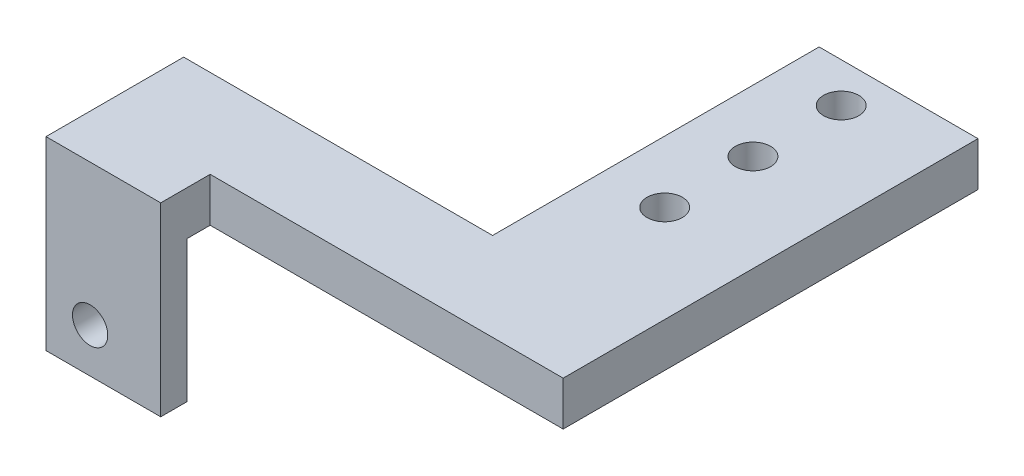
SolidWorks part; units mm, degrees
ref_plane "Alzado" through (0, 0, 0) normal (0, 0, 1) x (1, 0, 0)
ref_plane "Planta" through (0, 0, 0) normal (0, 1, 0) x (1, 0, 0)
ref_plane "Vista lateral" through (0, 0, 0) normal (1, 0, 0) x (0, 0, -1)
sketch "Croquis1" plane through (0, 0, 0) normal (0, 1, 0) x (1, 0, 0)
  line L0 (27.5, -11.1605) -> (-12.5, -11.1605)
  line L1 (-12.5, -16.7605) -> (-25.5, -16.7605)
  line L2 (27.5, -11.1605) -> (27.5, 35.8395)
  line L3 (27.5, 35.8395) -> (9.5, 35.8395)
  line L4 (-25.5, -16.7605) -> (-25.5, -1.1605)
  line L7 (-12.5, -11.1605) -> (-12.5, -16.7605)
  line L8 (-25.5, -1.1605) -> (9.5, -1.1605)
  line L9 (9.5, 35.8395) -> (9.5, -1.1605)
  point P0 (0, 0)
  dimension "D1" = 5.6
  dimension "D2" = 40
  dimension "D3" = 47
  dimension "D4" = 10
  dimension "D5" = 18
  dimension "D6" = 13
extrude "Saliente-Extruir1" add sketch "Croquis1" along normal blind 5
sketch "Croquis2" plane through (0, 0, 0) normal (0, -1, 0) x (-1, 0, 0)
  line L0 (25.5, -1.1605) -> (25.5, -16.7605) construction
  line L1 (12.5, -16.7605) -> (25.5, -16.7605)
  line L2 (12.5, -16.7605) -> (12.5, -13.7605)
  line L3 (12.5, -13.7605) -> (25.5, -13.7605)
  line L4 (25.5, -16.7605) -> (25.5, -13.7605)
  dimension "D1" = 3
extrude "Saliente-Extruir2" add sketch "Croquis2" along normal blind 16
sketch "Croquis3" plane through (0, 5, 0) normal (0, 1, 0) x (1, 0, 0)
  line L0 (14.5, -8.7441) -> (14.5, 49991.2559) construction
  line L1 (9.5, 35.8395) -> (9.5, -1.1605) construction
  line L2 (4.8587, 33.3395) -> (33.3046, 33.3395) construction
  line L3 (27.5, 35.8395) -> (9.5, 35.8395) construction
  line L4 (-8.5872, 21.3395) -> (5.6661, 21.3395) construction
  line L5 (-7.2297, 11.3395) -> (5.1725, 11.3395) construction
  circle A0 centre (16.5, 31.3395) radius 2
  circle A1 centre (16.5, 21.3395) radius 2
  circle A2 centre (16.5, 11.3395) radius 2
  dimension "D3" = 10
  dimension "D1" = 5
  dimension "D2" = 2.5
  dimension "D4" = 10
extrude "Cortar-Extruir1" cut sketch "Croquis3" against normal blind 16
sketch "Croquis7" plane through (0, 0, 13.7605) normal (0, 0, -1) x (-1, 0, 0)
  line L0 (18.1653, -13) -> (30.2995, -13) construction
  line L1 (22.5, -7.0168) -> (22.5, -17.2731) construction
  line L2 (25.5, -16) -> (25.5, 0) construction
  line L3 (25.5, -16) -> (12.5, -16) construction
  circle A0 centre (20.5, -11) radius 2
  dimension "D1" = 3
  dimension "D2" = 3
extrude "Cortar-Extruir2" cut sketch "Croquis7" against normal blind 16
